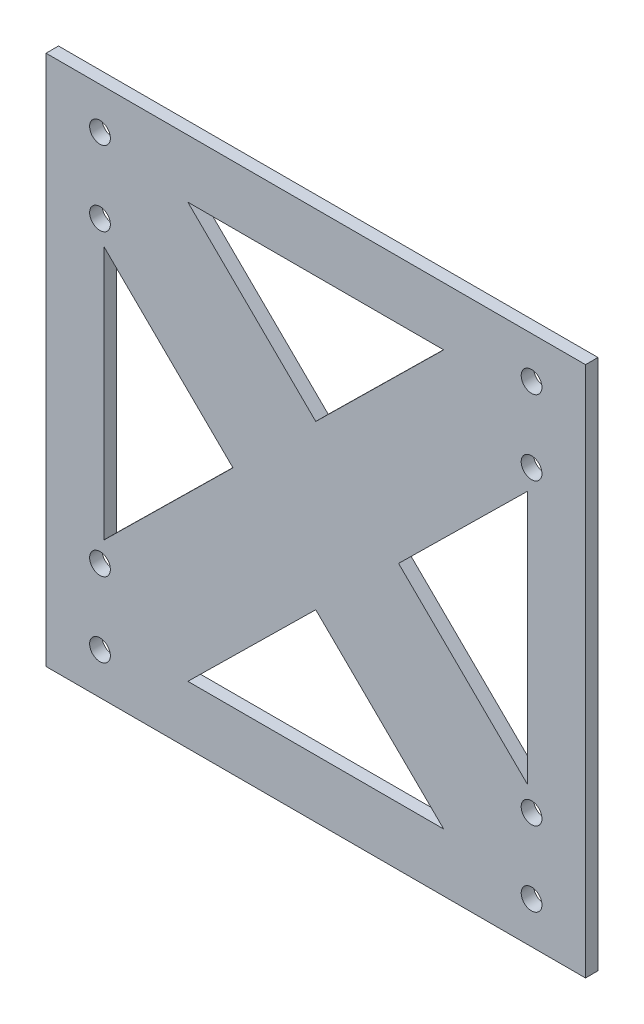
SolidWorks part; units mm, degrees
ref_plane "前基準面" through (0, 0, 0) normal (0, 0, 1) x (1, 0, 0)
ref_plane "上基準面" through (0, 0, 0) normal (0, 1, 0) x (1, 0, 0)
ref_plane "右基準面" through (0, 0, 0) normal (1, 0, 0) x (0, 0, -1)
sketch "草圖2" plane through (0, 0, 0) normal (0, 0, 1) x (1, 0, 0)
  line L0 (-65, 64) -> (0, 0) construction
  line L1 (-65, -64) -> (65, -64)
  line L2 (-65, -64) -> (-65, 64)
  line L3 (-65, 64) -> (65, 64)
  line L4 (65, -64) -> (65, 64)
  line L5 (-65, -64) -> (65, 64) construction
  line L6 (-65, 64) -> (65, -64) construction
  line L7 (0, 0) -> (65, 64) construction
  line L8 (-65, -64) -> (0, 0) construction
  line L9 (65, -64) -> (0, 0) construction
  line L10 (0, 19.6473) -> (30.827, 50)
  line L11 (-30.827, 50) -> (30.827, 50)
  line L12 (-30.827, 50) -> (0, 19.6473)
  line L13 (-51, 30.5681) -> (-19.9543, 0)
  line L14 (-51, -30.5681) -> (-19.9543, 0)
  line L15 (-51, -30.5681) -> (-51, 30.5681)
  line L16 (19.9543, 0) -> (51, 30.5681)
  line L17 (51, -30.5681) -> (51, 30.5681)
  line L18 (51, -30.5681) -> (19.9543, 0)
  line L19 (30.827, -50) -> (0, -19.6473)
  line L20 (-30.827, -50) -> (0, -19.6473)
  line L21 (-30.827, -50) -> (30.827, -50)
  point P0 (0, 0)
  dimension "D1" = 130
  dimension "D2" = 128
  dimension "D3" = 14
  dimension "D4" = 14
  dimension "D5" = 14
  dimension "13" = 14
extrude "填料-伸長1" add sketch "草圖2" along normal blind 3
ref_plane "平面1" through (0, 0, 0) normal (0, 0, -1) x (-1, 0, 0)
sketch "草圖3" plane through (0, 0, 0) normal (0, 0, -1) x (-1, 0, 0)
  line L0 (65, -64) -> (60, -64) construction
  line L1 (65, -64) -> (-65, -64) construction
  line L2 (-65, -64) -> (-60, -64) construction
  line L3 (-60, -64) -> (-52, -64) construction
  line L4 (60, -64) -> (52, -64) construction
  line L5 (-52, -64) -> (-52, -54) construction
  line L6 (52, -64) -> (52, -54) construction
  line L7 (-52, -54) -> (-52, -36) construction
  line L8 (52, -54) -> (52, -36) construction
  line L9 (-65, 64) -> (-60, 64) construction
  line L10 (-65, 64) -> (65, 64) construction
  line L11 (-60, 64) -> (-52, 64) construction
  line L12 (-52, 64) -> (-52, 54) construction
  line L13 (-52, 54) -> (-52, 36) construction
  line L14 (65, 64) -> (60, 64) construction
  line L15 (60, 64) -> (52, 64) construction
  line L16 (52, 64) -> (52, 54) construction
  line L17 (52, 54) -> (52, 36) construction
  circle A0 centre (-52, -54) radius 2.5
  circle A1 centre (-52, -36) radius 2.5
  circle A2 centre (52, -54) radius 2.5
  circle A3 centre (52, -36) radius 2.5
  circle A4 centre (-52, 54) radius 2.5
  circle A5 centre (-52, 36) radius 2.5
  circle A6 centre (52, 54) radius 2.5
  circle A7 centre (52, 36) radius 2.5
  dimension "D5" = 5
  dimension "D1" = 5
  dimension "D2" = 8
  dimension "D3" = 10
  dimension "D4" = 18
extrude "除料-伸長1" cut sketch "草圖3" against normal through all contours A0 | A1 | A2 | A3 | A5 | A4 | A6 | A7
